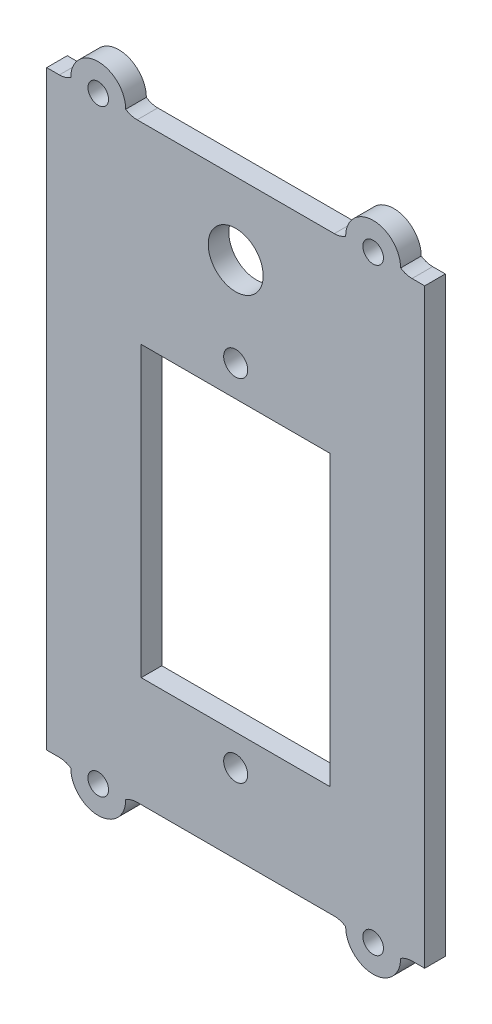
SolidWorks part; units mm, degrees
material "Aircraft Ply"
ref_plane "Front Plane" through (0, 0, 0) normal (0, 0, 1) x (1, 0, 0)
ref_plane "Top Plane" through (0, 0, 0) normal (0, 1, 0) x (1, 0, 0)
ref_plane "Right Plane" through (0, 0, 0) normal (1, 0, 0) x (0, 0, -1)
sketch "Sketch1" plane through (0, 0, 0) normal (0, 0, 1) x (1, 0, 0)
  line L10 (-10.6583, 43) -> (10.6583, 43)
  line L11 (-10.6583, -43) -> (10.6583, -43)
  line L14 (10.6583, -43) -> (14.3417, -43)
  line L15 (25.6583, -43) -> (27.5, -43)
  line L16 (27.5, -43) -> (27.5, 43)
  line L17 (27.5, 43) -> (25.6583, 43)
  line L18 (14.3417, 43) -> (10.6583, 43)
  line L20 (-10.6583, 43) -> (-14.3417, 43)
  line L21 (-25.6583, 43) -> (-27.5, 43)
  line L22 (-27.5, 43) -> (-27.5, -43)
  line L23 (-27.5, -43) -> (-25.6583, -43)
  line L24 (-14.3417, -43) -> (-10.6583, -43)
  line L26 (10.6583, -43) -> (14.3417, -43)
  line L27 (25.6583, -43) -> (27.5, -43)
  line L28 (27.5, -43) -> (27.5, 43)
  line L29 (27.5, 43) -> (25.6583, 43)
  line L30 (14.3417, 43) -> (10.6583, 43)
  line L32 (-10.6583, 43) -> (-14.3417, 43)
  line L33 (-25.6583, 43) -> (-27.5, 43)
  line L34 (-27.5, 43) -> (-27.5, -43)
  line L35 (-27.5, -43) -> (-25.6583, -43)
  line L36 (-14.3417, -43) -> (-10.6583, -43)
  circle A0 centre (-20, 43.5) radius 1.5
  circle A3 centre (20, 43.5) radius 1.5
  circle A4 centre (-20, -43.5) radius 1.5
  circle A7 centre (20, -43.5) radius 1.5
  arc A24 (-9, -43.5) -> (-1, -43.5) centre (-5, -43.5) ccw
  arc A25 (0, -43.0731) -> (-1, -43.5) centre (0.6583, -46) ccw
  arc A26 (1, -43.5) -> (0, -43.0731) centre (-0.6583, -46) ccw
  arc A27 (1, -43.5) -> (9, -43.5) centre (5, -43.5) ccw
  arc A28 (10.6583, -43) -> (9, -43.5) centre (10.6583, -46) ccw
  arc A29 (16, -43.5) -> (14.3417, -43) centre (14.3417, -46) ccw
  arc A30 (16, -43.5) -> (24, -43.5) centre (20, -43.5) ccw
  arc A31 (25.6583, -43) -> (24, -43.5) centre (25.6583, -46) ccw
  arc A32 (24, 43.5) -> (25.6583, 43) centre (25.6583, 46) ccw
  arc A33 (24, 43.5) -> (16, 43.5) centre (20, 43.5) ccw
  arc A34 (14.3417, 43) -> (16, 43.5) centre (14.3417, 46) ccw
  arc A35 (9, 43.5) -> (10.6583, 43) centre (10.6583, 46) ccw
  arc A36 (9, 43.5) -> (1, 43.5) centre (5, 43.5) ccw
  arc A37 (0, 43.0731) -> (1, 43.5) centre (-0.6583, 46) ccw
  arc A38 (-1, 43.5) -> (0, 43.0731) centre (0.6583, 46) ccw
  arc A39 (-1, 43.5) -> (-9, 43.5) centre (-5, 43.5) ccw
  arc A40 (-10.6583, 43) -> (-9, 43.5) centre (-10.6583, 46) ccw
  arc A41 (-16, 43.5) -> (-14.3417, 43) centre (-14.3417, 46) ccw
  arc A42 (-16, 43.5) -> (-24, 43.5) centre (-20, 43.5) ccw
  arc A43 (-25.6583, 43) -> (-24, 43.5) centre (-25.6583, 46) ccw
  arc A44 (-24, -43.5) -> (-25.6583, -43) centre (-25.6583, -46) ccw
  arc A45 (-24, -43.5) -> (-16, -43.5) centre (-20, -43.5) ccw
  arc A46 (-14.3417, -43) -> (-16, -43.5) centre (-14.3417, -46) ccw
  arc A47 (-9, -43.5) -> (-10.6583, -43) centre (-10.6583, -46) ccw
  arc A48 (-9, -43.5) -> (-1, -43.5) centre (-5, -43.5) ccw
  arc A49 (0, -43.0731) -> (-1, -43.5) centre (0.6583, -46) ccw
  arc A50 (1, -43.5) -> (0, -43.0731) centre (-0.6583, -46) ccw
  arc A51 (1, -43.5) -> (9, -43.5) centre (5, -43.5) ccw
  arc A52 (10.6583, -43) -> (9, -43.5) centre (10.6583, -46) ccw
  arc A53 (16, -43.5) -> (14.3417, -43) centre (14.3417, -46) ccw
  arc A54 (16, -43.5) -> (24, -43.5) centre (20, -43.5) ccw
  arc A55 (25.6583, -43) -> (24, -43.5) centre (25.6583, -46) ccw
  arc A56 (24, 43.5) -> (25.6583, 43) centre (25.6583, 46) ccw
  arc A57 (24, 43.5) -> (16, 43.5) centre (20, 43.5) ccw
  arc A58 (14.3417, 43) -> (16, 43.5) centre (14.3417, 46) ccw
  arc A59 (9, 43.5) -> (10.6583, 43) centre (10.6583, 46) ccw
  arc A60 (9, 43.5) -> (1, 43.5) centre (5, 43.5) ccw
  arc A61 (0, 43.0731) -> (1, 43.5) centre (-0.6583, 46) ccw
  arc A62 (-1, 43.5) -> (0, 43.0731) centre (0.6583, 46) ccw
  arc A63 (-1, 43.5) -> (-9, 43.5) centre (-5, 43.5) ccw
  arc A64 (-10.6583, 43) -> (-9, 43.5) centre (-10.6583, 46) ccw
  arc A65 (-16, 43.5) -> (-14.3417, 43) centre (-14.3417, 46) ccw
  arc A66 (-16, 43.5) -> (-24, 43.5) centre (-20, 43.5) ccw
  arc A67 (-25.6583, 43) -> (-24, 43.5) centre (-25.6583, 46) ccw
  arc A68 (-24, -43.5) -> (-25.6583, -43) centre (-25.6583, -46) ccw
  arc A69 (-24, -43.5) -> (-16, -43.5) centre (-20, -43.5) ccw
  arc A70 (-14.3417, -43) -> (-16, -43.5) centre (-14.3417, -46) ccw
  arc A71 (-9, -43.5) -> (-10.6583, -43) centre (-10.6583, -46) ccw
  dimension "D2" = 3
  dimension "D1" = 0
extrude "Boss-Extrude1" add sketch "Sketch1" along normal blind 3 contours A70 L36 L11 L26 A53 A54 A55 L27 L28 L29 A56 A57 A58 L30 L10 L32 A65 A66 A67 L33 L34 L35 A68 A69 A7 A4 A3 A0
sketch "Sketch2" plane through (0, 0, 0) normal (0, 0, 1) x (1, 0, 0)
  line L0 (0, 0) -> (0, 32.5) construction
  line L1 (0, 0) -> (0, -44.7304) construction
  line L4 (-13.75, 15) -> (13.75, 15)
  line L5 (-13.75, 15) -> (-13.75, -27)
  line L6 (-13.75, -27) -> (13.75, -27)
  line L7 (13.75, 15) -> (13.75, -27)
  line L8 (-13.75, 15) -> (13.75, -27) construction
  line L9 (-13.75, -27) -> (13.75, 15) construction
  circle A0 centre (0, 32.5) radius 4
  circle A1 centre (0, 19.5) radius 1.75
  circle A2 centre (0, -31.5) radius 1.75
  point P4 (0, -6)
  point P6 (0, -44.7304)
  dimension "D1" = 8
  dimension "D8" = 3.5
  dimension "D2" = 32.5
  dimension "D3" = 42
  dimension "D4" = 27.5
  dimension "D5" = 6
  dimension "D6" = 4.5
  dimension "D7" = 4.5
extrude "Cut-Extrude1" cut sketch "Sketch2" along normal through all
